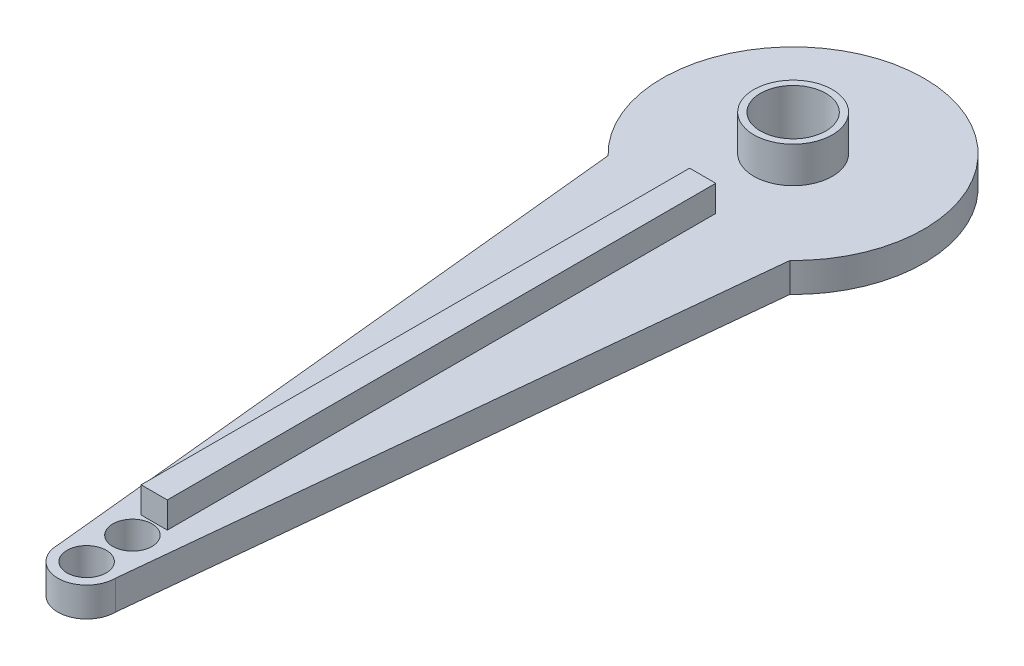
SolidWorks part; units mm, degrees
material "Prusament PETG"
ref_plane "Front Plane" through (0, 0, 0) normal (0, 0, 1) x (1, 0, 0)
ref_plane "Top Plane" through (0, 0, 0) normal (0, 1, 0) x (1, 0, 0)
ref_plane "Right Plane" through (0, 0, 0) normal (1, 0, 0) x (0, 0, -1)
sketch "Sketch1" plane through (0, 0, 0) normal (0, 1, 0) x (1, 0, 0)
  line L0 (0, 0) -> (0, 3) construction
  line L1 (0, 0) -> (0, -54) construction
  line L4 (0, 0) -> (0, 19) construction
  line L5 (-3.75, 3.8856) -> (10.1389, 3.8856) construction
  line L6 (2.2, -54) -> (6.9444, -7.1955)
  line L7 (6.9444, -7.1955) -> (-6.9444, -7.1955) construction
  line L8 (-6.9444, -7.1955) -> (-2.2, -54)
  circle A0 centre (0, 0) radius 3
  arc A2 (-2.2, -54) -> (2.2, -54) centre (0, -54) ccw
  circle A5 centre (0, -54) radius 1.5
  circle A10 centre (0, -50.5) radius 1.5
  arc A13 (6.9444, -7.1955) -> (-6.9444, -7.1955) centre (0, 0) ccw
  point P10 (0, -27)
  dimension "D1" = 6
  dimension "D2" = 54
  dimension "D6" = 3
  dimension "D13" = 3.5
  dimension "D3" = 10
  dimension "D5" = 2.2
extrude "Boss-Extrude1" add sketch "Sketch1" along normal blind 2.25
sketch "Sketch2" plane through (0, 2.25, 0) normal (0, 1, 0) x (1, 0, 0)
  line L0 (1.96, 0) -> (2.3493, 0.2247)
  line L1 (2.3493, -0.2247) -> (1.96, 0)
  line L2 (1.8984, 0.4874) -> (2.2196, 0.8019)
  line L3 (2.3314, 0.3666) -> (1.8984, 0.4874)
  line L4 (-0.3673, -1.9253) -> (-0.2194, -2.3498)
  line L5 (-0.661, -2.2655) -> (-0.3673, -1.9253)
  line L6 (0.1231, -1.9561) -> (0.3718, -2.3305)
  line L7 (-0.0768, -2.3588) -> (0.1231, -1.9561)
  line L8 (0.6057, -1.8641) -> (0.9397, -2.1648)
  line L9 (0.5122, -2.3037) -> (0.6057, -1.8641)
  line L10 (1.0502, -1.6549) -> (1.4486, -1.8631)
  line L11 (1.069, -2.104) -> (1.0502, -1.6549)
  line L12 (1.4288, -1.3417) -> (1.8664, -1.4444)
  line L13 (1.5587, -1.772) -> (1.4288, -1.3417)
  line L14 (1.7176, -0.9442) -> (2.167, -0.9348)
  line L15 (1.9504, -1.3287) -> (1.7176, -0.9442)
  line L16 (1.8984, -0.4874) -> (2.3314, -0.3666)
  line L17 (2.2196, -0.8019) -> (1.8984, -0.4874)
  line L18 (0.6057, 1.8641) -> (0.5122, 2.3037)
  line L19 (0.9397, 2.1648) -> (0.6057, 1.8641)
  line L20 (1.0502, 1.6549) -> (1.069, 2.104)
  line L21 (1.4486, 1.8631) -> (1.0502, 1.6549)
  line L22 (1.4288, 1.3417) -> (1.5587, 1.772)
  line L23 (1.8664, 1.4444) -> (1.4288, 1.3417)
  line L24 (1.7176, 0.9442) -> (1.9504, 1.3287)
  line L25 (2.167, 0.9348) -> (1.7176, 0.9442)
  line L26 (0.1231, 1.9561) -> (-0.0768, 2.3588)
  line L27 (0.3718, 2.3305) -> (0.1231, 1.9561)
  line L28 (-0.3673, 1.9253) -> (-0.661, 2.2655)
  line L29 (-0.2194, 2.3498) -> (-0.3673, 1.9253)
  line L30 (-0.8345, 1.7735) -> (-1.2036, 2.03)
  line L31 (-0.7969, 2.2214) -> (-0.8345, 1.7735)
  line L32 (-1.2494, 1.5102) -> (-1.6707, 1.6669)
  line L33 (-1.3243, 1.9534) -> (-1.2494, 1.5102)
  line L34 (-1.5857, 1.1521) -> (-2.0327, 1.199)
  line L35 (-1.7685, 1.5627) -> (-1.5857, 1.1521)
  line L36 (-1.8224, 0.7215) -> (-2.267, 0.6559)
  line L37 (-2.1016, 1.0738) -> (-1.8224, 0.7215)
  line L38 (-1.9445, 0.2457) -> (-2.3589, 0.0715)
  line L39 (-2.3026, 0.5174) -> (-1.9445, 0.2457)
  line L40 (-1.9445, -0.2457) -> (-2.3026, -0.5174)
  line L41 (-2.3589, -0.0715) -> (-1.9445, -0.2457)
  line L42 (-0.8345, -1.7735) -> (-0.7969, -2.2214)
  line L43 (-1.2036, -2.03) -> (-0.8345, -1.7735)
  line L44 (-1.2494, -1.5102) -> (-1.3243, -1.9534)
  line L45 (-1.6707, -1.6669) -> (-1.2494, -1.5102)
  line L46 (-1.5857, -1.1521) -> (-1.7685, -1.5627)
  line L47 (-2.0327, -1.199) -> (-1.5857, -1.1521)
  line L48 (-1.8224, -0.7215) -> (-2.1016, -1.0738)
  line L49 (-2.267, -0.6559) -> (-1.8224, -0.7215)
  line L50 (0, 0) -> (-0.1482, 2.3553) construction
  line L51 (-0.1482, 2.3553) -> (0.1231, -1.9561) construction
  circle A1 centre (0, 0) radius 3.8795
  arc A2 (-2.1016, -1.0738) -> (-2.0327, -1.199) centre (0, 0) ccw
  arc A3 (-1.7685, -1.5627) -> (-1.6707, -1.6669) centre (0, 0) ccw
  arc A4 (-1.3243, -1.9534) -> (-1.2036, -2.03) centre (0, 0) ccw
  arc A5 (-0.7969, -2.2214) -> (-0.661, -2.2655) centre (0, 0) ccw
  arc A6 (-2.3026, -0.5174) -> (-2.267, -0.6559) centre (0, 0) ccw
  arc A7 (-2.3589, 0.0715) -> (-2.3589, -0.0715) centre (0, 0) ccw
  arc A8 (-2.267, 0.6559) -> (-2.3026, 0.5174) centre (0, 0) ccw
  arc A9 (-2.0327, 1.199) -> (-2.1016, 1.0738) centre (0, 0) ccw
  arc A10 (-1.6707, 1.6669) -> (-1.7685, 1.5627) centre (0, 0) ccw
  arc A11 (-1.2036, 2.03) -> (-1.3243, 1.9534) centre (0, 0) ccw
  arc A12 (-0.661, 2.2655) -> (-0.7969, 2.2214) centre (0, 0) ccw
  arc A13 (-0.0768, 2.3588) -> (-0.2194, 2.3498) centre (0, 0) ccw
  arc A14 (1.9504, 1.3287) -> (1.8664, 1.4444) centre (0, 0) ccw
  arc A15 (1.5587, 1.772) -> (1.4486, 1.8631) centre (0, 0) ccw
  arc A16 (1.069, 2.104) -> (0.9397, 2.1648) centre (0, 0) ccw
  arc A17 (0.5122, 2.3037) -> (0.3718, 2.3305) centre (0, 0) ccw
  arc A18 (2.3314, -0.3666) -> (2.3493, -0.2247) centre (0, 0) ccw
  arc A19 (2.167, -0.9348) -> (2.2196, -0.8019) centre (0, 0) ccw
  arc A20 (1.8664, -1.4444) -> (1.9504, -1.3287) centre (0, 0) ccw
  arc A21 (1.4486, -1.8631) -> (1.5587, -1.772) centre (0, 0) ccw
  arc A22 (0.9397, -2.1648) -> (1.069, -2.104) centre (0, 0) ccw
  arc A23 (0.3718, -2.3305) -> (0.5122, -2.3037) centre (0, 0) ccw
  arc A24 (-0.2194, -2.3498) -> (-0.0768, -2.3588) centre (0, 0) ccw
  arc A25 (2.2196, 0.8019) -> (2.167, 0.9348) centre (0, 0) ccw
  arc A26 (2.3493, 0.2247) -> (2.3314, 0.3666) centre (0, 0) ccw
extrude "Boss-Extrude2" add sketch "Sketch2" along normal blind 2.25
sketch "Sketch3" plane through (0, 0, 0) normal (0, -1, 0) x (1, 0, 0)
  circle A0 centre (0, 0) radius 2.0085
  circle A1 centre (0, 0) radius 3
  circle A2 centre (0, 0) radius 3 construction
extrude "Boss-Extrude3" add sketch "Sketch3" against normal blind 1
sketch "Sketch4" plane through (0, 0, 0) normal (0, -1, 0) x (1, 0, 0)
  circle A0 centre (0, 0) radius 3
  circle A1 centre (0, 0) radius 3.8
  dimension "D1" = 0.8
  dimension "D2" = 6
extrude "Cut-Extrude1" cut sketch "Sketch4" against normal blind 0.5
sketch "Sketch5" plane through (0, 2.25, 0) normal (0, 1, 0) x (1, 0, 0)
  line L0 (0, -3.8795) -> (0, -49) construction
  line L2 (-1, -48.8344) -> (1, -48.8344)
  line L3 (-1, -48.8344) -> (-1, -3.7484)
  line L4 (-1, -3.7484) -> (1, -3.7484)
  line L5 (1, -48.8344) -> (1, -3.7484)
  line L6 (-1, -48.8344) -> (1, -3.7484) construction
  line L7 (-1, -3.7484) -> (1, -48.8344) construction
  circle A0 centre (0, 0) radius 3.8795 construction
  circle A1 centre (0, -50.5) radius 1.5 construction
  point P7 (0, -26.2914)
  dimension "D1" = 2
extrude "Boss-Extrude4" add sketch "Sketch5" along normal blind 2
sketch "Sketch6" plane through (0, 4.5, 0) normal (0, 1, 0) x (1, 0, 0)
  circle A0 centre (0, 0) radius 3.8795
sketch "Sketch7" plane through (0, 4.5, 0) normal (0, 1, 0) x (1, 0, 0)
  circle A0 centre (0, 0) radius 3.8795
extrude "Cut-Extrude2" cut sketch "Sketch7" against normal up to surface (2.25 mm away) up to face at (0, 2.25, 55.5)
sketch "Sketch8" plane through (0, 1, 0) normal (0, 1, 0) x (1, 0, 0)
  circle A0 centre (0, 0) radius 3
  circle A1 centre (0, 0) radius 2.5
extrude "Boss-Extrude5" add sketch "Sketch8" along normal blind 4
sketch "Sketch9" plane through (0, 4.25, 0) normal (0, 1, 0) x (1, 0, 0)
  line L0 (1, -48.8344) -> (1, -3.7484) construction
  line L1 (-1, -3.7484) -> (1, -3.7484)
  line L2 (-1, -3.7484) -> (-1, -6.9147)
  line L3 (-1, -6.9147) -> (1, -6.9147)
  line L4 (1, -3.7484) -> (1, -6.9147)
extrude "Cut-Extrude3" cut sketch "Sketch9" against normal up to surface (2 mm away) up to face at (0, 2.25, 55.5)
